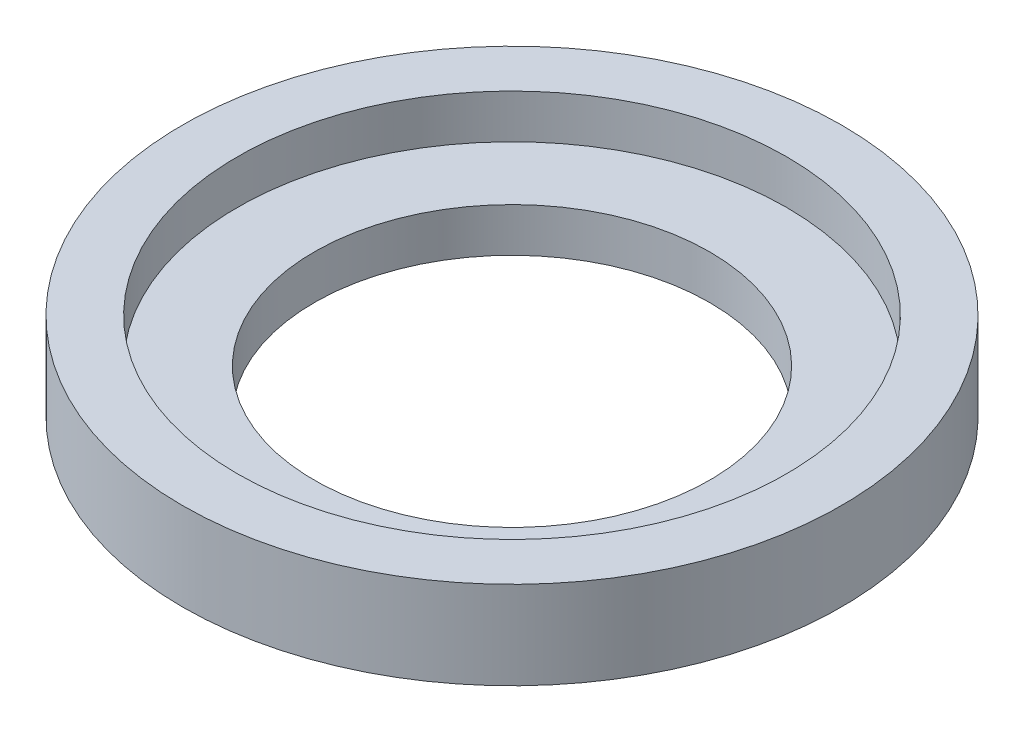
SolidWorks part; units mm, degrees
ref_plane "Front Plane" through (0, 0, 0) normal (0, 0, 1) x (1, 0, 0)
ref_plane "Top Plane" through (0, 0, 0) normal (0, 1, 0) x (1, 0, 0)
ref_plane "Right Plane" through (0, 0, 0) normal (1, 0, 0) x (0, 0, -1)
sketch "Sketch1" plane through (0, 0, 0) normal (0, 0, 1) x (1, 0, 0)
  line L0 (9, 0) -> (9, 2)
  line L1 (9, 2) -> (12.5, 2)
  line L2 (12.5, 2) -> (12.5, 4)
  line L3 (12.5, 4) -> (15, 4)
  line L4 (15, 4) -> (15, 0)
  line L5 (15, 0) -> (9, 0)
  line L6 (0, 0) -> (0, 3.7428) construction
  dimension "D1" = 9
  dimension "D2" = 12.5
  dimension "D3" = 15
  dimension "D4" = 4
  dimension "D5" = 2
revolve "Revolve1" add sketch "Sketch1" angle 360 about L6
